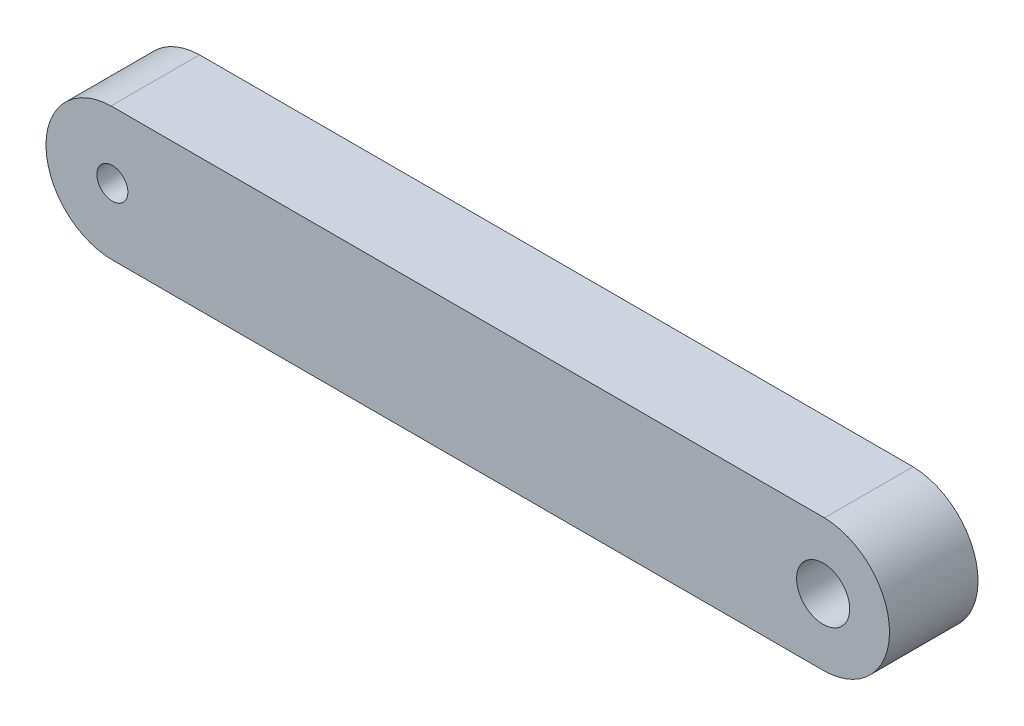
SolidWorks part; units mm, degrees
ref_plane "前视基准面" through (0, 0, 0) normal (0, 0, 1) x (1, 0, 0)
ref_plane "上视基准面" through (0, 0, 0) normal (0, 1, 0) x (1, 0, 0)
ref_plane "右视基准面" through (0, 0, 0) normal (1, 0, 0) x (0, 0, -1)
sketch "草图1" plane through (0, 0, 0) normal (0, 0, 1) x (1, 0, 0)
  line L1 (-47.2764, 9.8232) -> (33.3316, 9.8232)
  line L3 (-46.9724, -5.1737) -> (33.0276, -5.1737)
  line L5 (-6.9724, -5.1737) -> (-6.9724, 9.8232) construction
  line L6 (-47.1244, 2.3247) -> (33.1796, 2.3247) construction
  circle A0 centre (-47.1244, 2.3247) radius 1.75
  circle A1 centre (-47.1244, 2.3247) radius 7.5
  circle A2 centre (33.1796, 2.3247) radius 7.5
  circle A4 centre (33.1796, 2.3247) radius 3
  point P0 (-6.9724, 2.3247)
  point P8 (0, 0)
  point P10 (-6.9724, 1.709)
  point P13 (-11.7041, 1.7856)
  dimension "D3" = 2
  dimension "D1" = 80
  dimension "D2" = 15
extrude "凸台-拉伸2" add sketch "草图1" along normal blind 10 contours L1 A1 A0 | A2 L1 A1 L3 | L1 A2 A4
